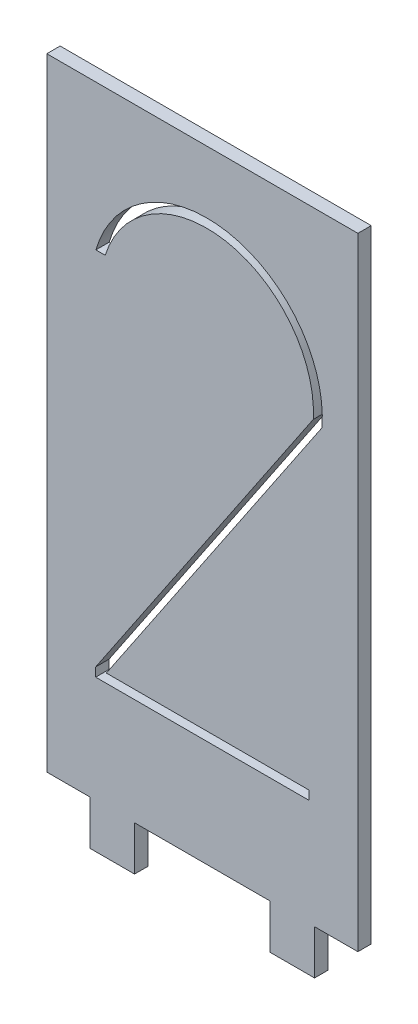
SolidWorks part; units mm, degrees
material "Glas"
ref_plane "Ebene vorne" through (0, 0, 0) normal (0, 0, 1) x (1, 0, 0)
ref_plane "Ebene oben" through (0, 0, 0) normal (0, 1, 0) x (1, 0, 0)
ref_plane "Ebene rechts" through (0, 0, 0) normal (1, 0, 0) x (0, 0, -1)
sketch "Skizze1" plane through (0, 0, 0) normal (0, 0, 1) x (1, 0, 0)
  line L1 (0, 0) -> (35, 0)
  line L2 (0, 0) -> (0, 75)
  line L3 (0, 75) -> (35, 75)
  line L4 (35, 0) -> (35, 75)
  dimension "D1" = 35
  dimension "D2" = 75
extrude "Aufsatz-Linear austragen1" add sketch "Skizze1" along normal blind 1.5
sketch "Skizze3" plane through (0, 0, 1.5) normal (0, 0, 1) x (1, 0, 0)
  line L0 (0, 0) -> (35, 0) construction
  line L1 (9.875, 0) -> (25.125, 0)
  line L2 (9.875, 0) -> (9.875, 5)
  line L3 (9.875, 5) -> (25.125, 5)
  line L4 (25.125, 0) -> (25.125, 5)
  line L5 (35, 0) -> (35, 75) construction
  line L6 (30.125, 5) -> (35, 5)
  line L7 (30.125, 5) -> (30.125, 0)
  line L8 (30.125, 0) -> (35, 0)
  line L9 (35, 5) -> (35, 0)
  line L10 (4.875, 5) -> (0, 5)
  line L11 (4.875, 5) -> (4.875, 0)
  line L12 (4.875, 0) -> (0, 0)
  line L13 (0, 5) -> (0, 0)
  dimension "D1" = 4.875
  dimension "D2" = 4.875
  dimension "D3" = 0
  dimension "D4" = 5
  dimension "D5" = 5
  dimension "D6" = 5
  dimension "D7" = 5
extrude "Schnitt-Linear austragen12" cut sketch "Skizze3" against normal blind 20
sketch "Skizze7" plane through (0, 0, 1.5) normal (0, 0, 1) x (1, 0, 0)
  line L0 (29.9828, 54.3572) -> (5.5, 18)
  line L1 (5.5, 18) -> (5.5, 17)
  line L2 (5.5, 17) -> (29.5, 17)
  line L3 (29.5, 17) -> (29.5, 18)
  line L4 (29.5, 18) -> (6.7, 18)
  line L5 (6.7, 18) -> (30.9639, 54.0322)
  line L6 (6.5662, 58.6426) -> (5.5208, 58.6426)
  line L7 (35, 5) -> (35, 75) construction
  line L8 (35, 75) -> (0, 75) construction
  line L9 (25.125, 5) -> (9.875, 5) construction
  line L10 (0, 75) -> (0, 5) construction
  arc A0 (5.5208, 58.6426) -> (30.9639, 54.0322) centre (18, 55) cw
  arc A1 (6.5662, 58.6426) -> (29.9828, 54.3572) centre (18, 55) cw
  dimension "D1" = 12
  dimension "D2" = 17
  dimension "13" = 13
  dimension "D3" = 20
  dimension "D4" = 12
  dimension "D5" = 1.2
  dimension "D6" = 1
  dimension "D7" = 5.5
  dimension "D8" = 5.5
extrude "Schnitt-Linear austragen14" cut sketch "Skizze7" against normal blind 1.5
